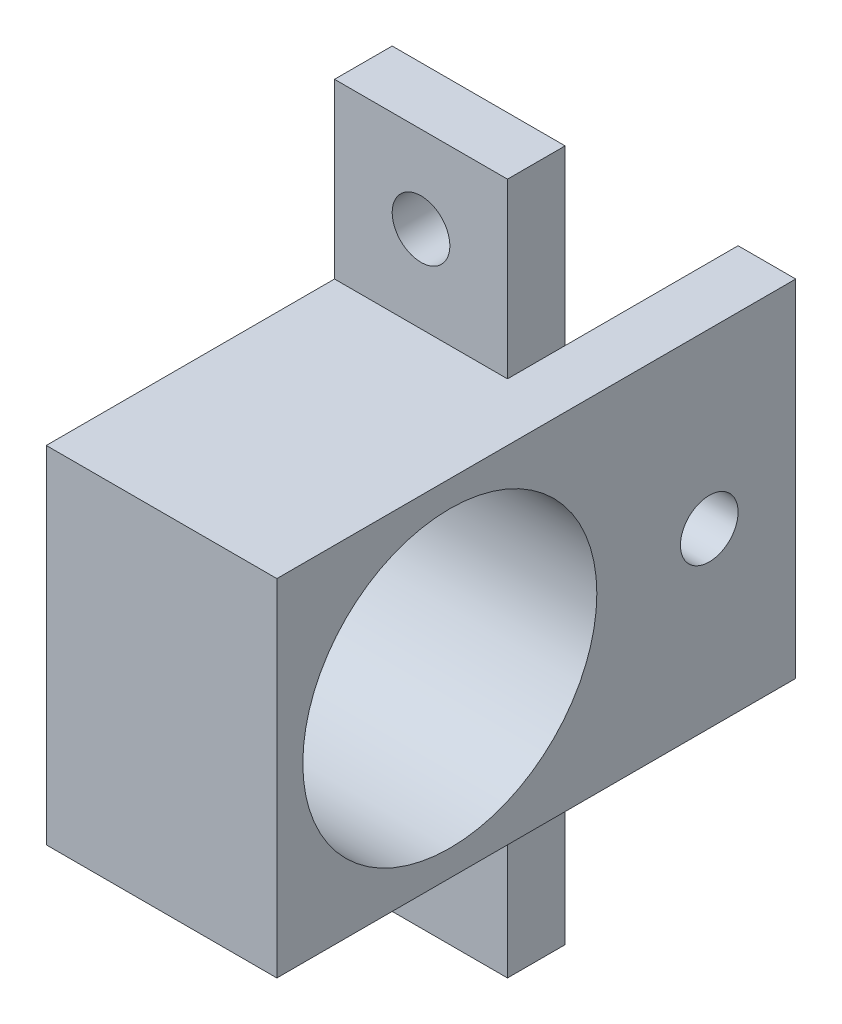
SolidWorks part; units mm, degrees
ref_plane "Front Plane" through (0, 0, 0) normal (1, 0, 0) x (0, 1, 0)
ref_plane "Top Plane" through (0, 0, 0) normal (0, 0, 1) x (0, 1, 0)
ref_plane "Right Plane" through (0, 0, 0) normal (0, 1, 0) x (-1, 0, 0)
sketch "Sketch1" plane through (0, 0, 0) normal (0, 0, 1) x (0, 1, 0)
  line L1 (0, 0) -> (30, 0)
  line L2 (0, 0) -> (0, 15)
  line L3 (0, 15) -> (30, 15)
  line L4 (30, 0) -> (30, 15)
  dimension "D1" = 15
  dimension "D2" = 30
extrude "Boss-Extrude1" add sketch "Sketch1" along normal blind 30 contours L1 L4 L3 L2
sketch "Sketch2" plane through (0, 0, 0) normal (1, 0, 0) x (0, 1, 0)
  line L1 (0, 30) -> (30, 30)
  line L2 (0, 30) -> (0, -15)
  line L3 (0, -15) -> (30, -15)
  line L4 (30, 30) -> (30, -15)
  line L6 (30, 30) -> (30, 0) construction
  line L7 (0, 0) -> (30, 0) construction
  point P7 (30, 0)
  dimension "D1" = 15
extrude "Boss-Extrude2" add sketch "Sketch2" along normal blind 5
sketch "Sketch3" plane through (5, 0, 0) normal (1, 0, 0) x (0, 1, 0)
  line L3 (30, 30) -> (0, 30) construction
  line L12 (15, 15) -> (15, 30)
  circle A2 centre (15, 15) radius 15
  circle A3 centre (15, 15) radius 12.75
  dimension "D1" = 30
sketch "Sketch5" plane through (5, 0, 0) normal (1, 0, 0) x (0, 1, 0)
  line L0 (0, 0) -> (30, 0) construction
  line L2 (30, -15) -> (30, 0) construction
  circle A0 centre (15, -7.5) radius 2.5
  dimension "D1" = 5
  dimension "D2" = 7.5
  dimension "D3" = 15
extrude "Cut-Extrude2" cut sketch "Sketch5" against normal through all
extrude "Cut-Extrude3" cut sketch "Sketch3" against normal through all contours A3
sketch "Sketch8" plane through (0, 0, 0) normal (0, 0, -1) x (1, 0, 0)
  line L0 (0, 0) -> (-15, 0) construction
  line L1 (-15, 0) -> (-15, -30) construction
  line L3 (-15, -30) -> (0, -30)
  line L4 (-15, -30) -> (-15, -45)
  line L5 (-15, -45) -> (0, -45)
  line L6 (0, -30) -> (0, -45)
  line L7 (-15, 0) -> (0, 0)
  line L8 (-15, 0) -> (-15, 15)
  line L9 (-15, 15) -> (0, 15)
  line L10 (0, 0) -> (0, 15)
  circle A0 centre (-7.5, -15) radius 2.5
  circle A1 centre (-7.5, -37.5) radius 2.5
  circle A2 centre (-7.5, 7.5) radius 2.5
  line M1 (0, 0) -> (-15, 0)
  line M3 (-15, -30) -> (0, -30)
  dimension "D1" = 5
  dimension "D4" = 5
  dimension "D5" = 5
  dimension "D2" = 15
  dimension "D3" = 7.5
  dimension "D6" = 15
  dimension "D7" = 15
  dimension "D8" = 7.5
  dimension "D9" = 7.5
extrude "Boss-Extrude4" add sketch "Sketch8" against normal blind 5 contours L6 L4 L5 A1 M3 | L10 L9 L8 A2 M1
